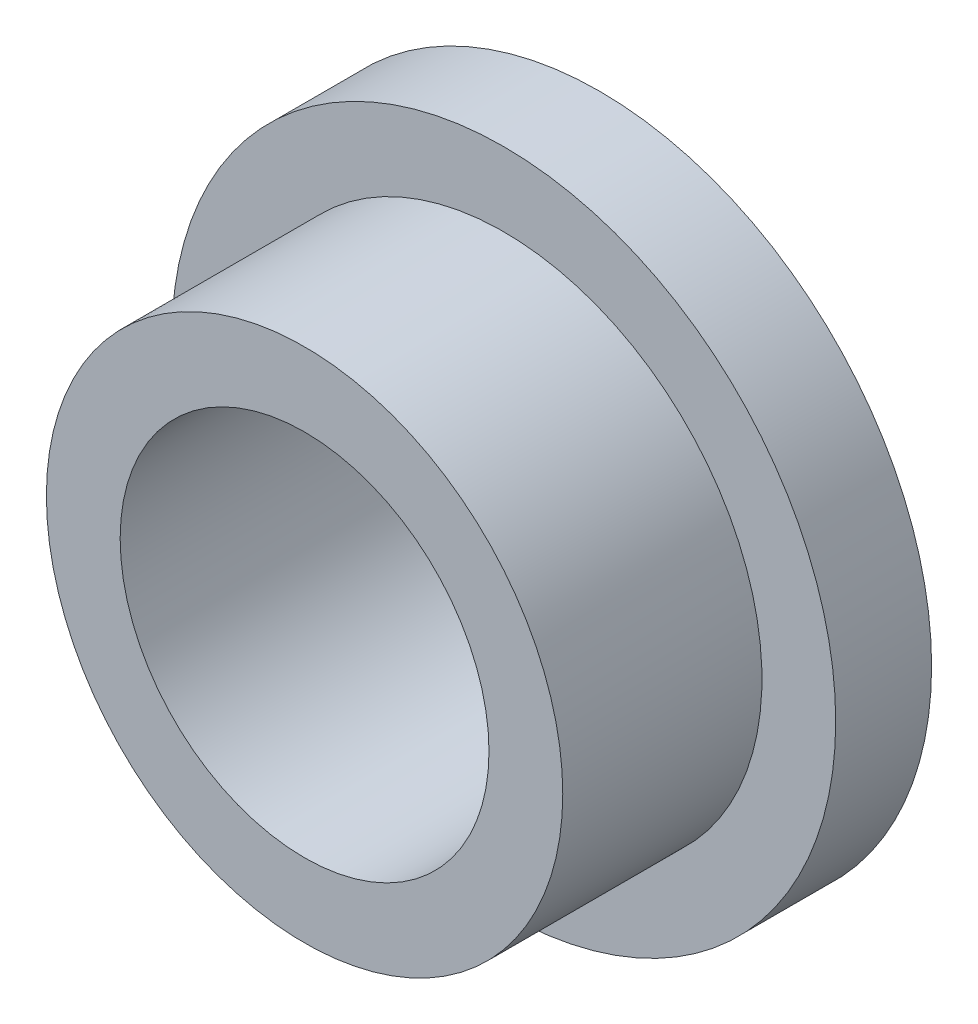
SolidWorks part; units mm, degrees
ref_plane "前视基准面" through (0, 0, 0) normal (0, 0, 1) x (1, 0, 0)
ref_plane "上视基准面" through (0, 0, 0) normal (0, 1, 0) x (1, 0, 0)
ref_plane "右视基准面" through (0, 0, 0) normal (1, 0, 0) x (0, 0, -1)
other "Configuration Table"
sketch "草图1" plane through (0, 0, 0) normal (0, 0, 1) x (1, 0, 0)
  circle A0 centre (0, 0) radius 7.5
  dimension "D1" = 15
extrude "拉伸-薄壁1" add sketch "草图1" along normal blind 12 thin
sketch "草图2" plane through (0, 0, 0) normal (0, 0, -1) x (-1, 0, 0)
  circle A0 centre (0, 0) radius 10.5
extrude "拉伸-薄壁2" add sketch "草图2" against normal blind 3.9 thin
